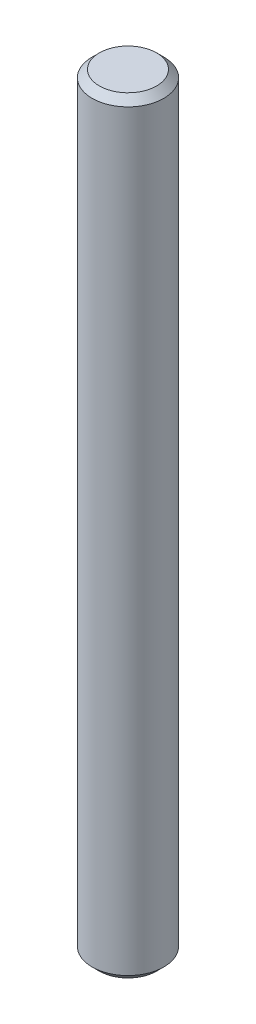
SolidWorks part; units mm, degrees
ref_plane "Спереди" through (0, 0, 0) normal (0, 0, 1) x (1, 0, 0)
ref_plane "Сверху" through (0, 0, 0) normal (0, 1, 0) x (1, 0, 0)
ref_plane "Справа" through (0, 0, 0) normal (1, 0, 0) x (0, 0, -1)
sketch "Эскиз1" plane through (0, 0, 0) normal (0, 1, 0) x (1, 0, 0)
  circle A0 centre (0, 0) radius 2.5
extrude "Бобышка-Вытянуть1" add sketch "Эскиз1" along normal blind 53.5
sketch "Эскиз2" plane through (0, 53.5, 0) normal (0, 1, 0) x (1, 0, 0)
  line L0 (0, -2.5) -> (-4.2999, -2.5) construction
  line L1 (-1.5, 2) -> (1.5, 2)
  circle A0 centre (0, 0) radius 2.5 construction
  arc A1 (1.5, 2) -> (-1.5, 2) centre (0, 0) ccw
  dimension "D1" = 4.5
  dimension "D2" = 5
extrude "Вырез-Вытянуть1" [suppressed] cut sketch "Эскиз2" against normal blind 15
chamfer "Фаска1" distance 0.5 angle 45 2 edges at (0, 53.5, 2.5) (0, 0, 2.5)
